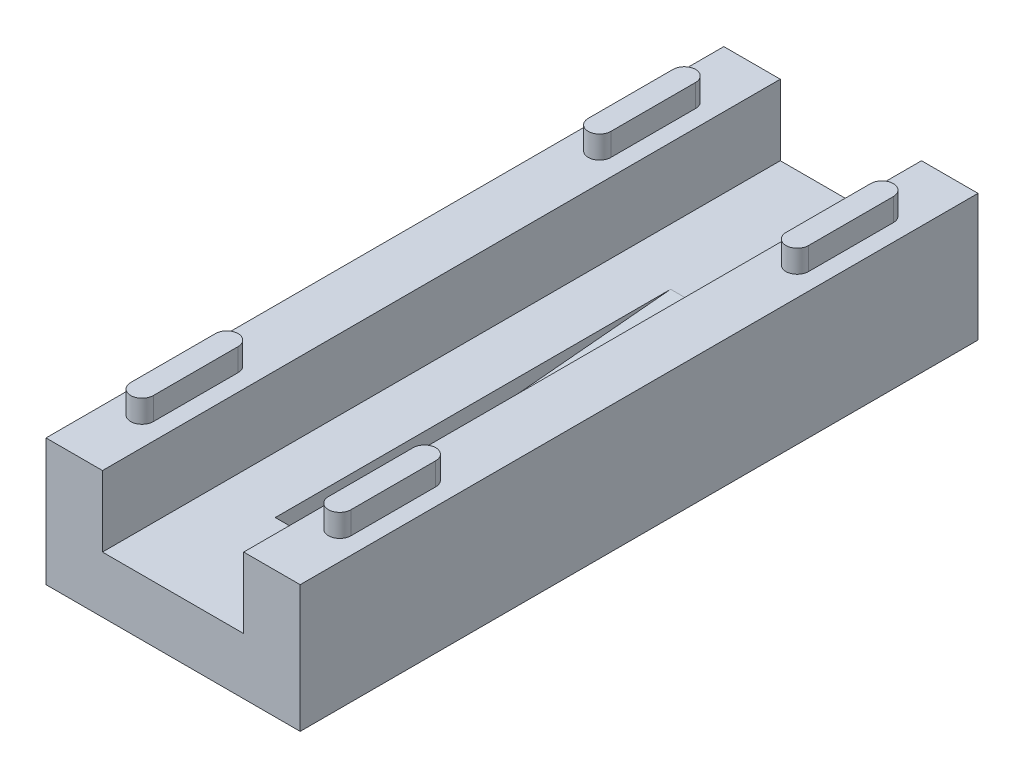
SolidWorks part; units mm, degrees
ref_plane "Front Plane" through (0, 0, 0) normal (0, 0, 1) x (1, 0, 0)
ref_plane "Top Plane" through (0, 0, 0) normal (0, 1, 0) x (1, 0, 0)
ref_plane "Right Plane" through (0, 0, 0) normal (1, 0, 0) x (0, 0, -1)
sketch "Sketch1" plane through (0, 0, 0) normal (0, 0, 1) x (1, 0, 0)
  line L0 (-12.5, 12.5) -> (-22.5, 12.5)
  line L1 (-22.5, 12.5) -> (-22.5, -10)
  line L2 (-22.5, -10) -> (22.5, -10)
  line L3 (22.5, -10) -> (22.5, 12.5)
  line L4 (22.5, 12.5) -> (12.5, 12.5)
  line L5 (12.5, 12.5) -> (12.5, 0)
  line L6 (12.5, 0) -> (-12.5, 0)
  line L7 (-12.5, 0) -> (-12.5, 12.5)
  line L8 (0, 0) -> (0, -10) construction
  dimension "D1" = 12.5
  dimension "D2" = 25
  dimension "D3" = 10
extrude "Boss-Extrude1" add sketch "Sketch1" along normal blind 120
sketch "Sketch2" plane through (0, 0, 0) normal (1, 0, 0) x (0, 0, -1)
  line L0 (-29.4165, 0) -> (-99.4165, 0)
  line L3 (-99.4165, 0) -> (-99.4165, -6.5)
  line L4 (-99.4165, -6.5) -> (-29.4165, 0)
  line L5 (-120, 12.5) -> (-120, 0) construction
  dimension "D1" = 6.5
  dimension "D2" = 70
  dimension "D3" = 20.5835
extrude "Cut-Extrude1" cut sketch "Sketch2" against normal blind 2.5 and the other way blind 2.5
sketch "Sketch3" plane through (0, 12.5, 0) normal (0, 1, 0) x (1, 0, 0)
  line L0 (-19.5, -108) -> (-19.5, -93)
  line L1 (-12.5, -120) -> (-22.5, -120) construction
  line L2 (-15.5, -93) -> (-15.5, -108)
  arc A0 (-15.5, -93) -> (-19.5, -93) centre (-17.5, -93) ccw
  arc A1 (-15.5, -108) -> (-19.5, -108) centre (-17.5, -108) cw
  point P8 (-17.5, -120)
  dimension "D2" = 2
  dimension "D1" = 15
  dimension "D3" = 10
extrude "Boss-Extrude2" add sketch "Sketch3" along normal blind 4
ref_plane "Plane1" through (0, 0, 0) normal (1, 0, 0) x (0, -1, 0)
mirror "Mirror1" about plane through (0, 0, 0) normal (1, 0, 0) of "Boss-Extrude2"
ref_plane "Plane2" through (0, 0, 60) normal (0, 0, -1) x (-1, 0, 0)
mirror "Mirror2" about plane through (0, 0, 60) normal (0, 0, -1) of "Mirror1", "Boss-Extrude2"
